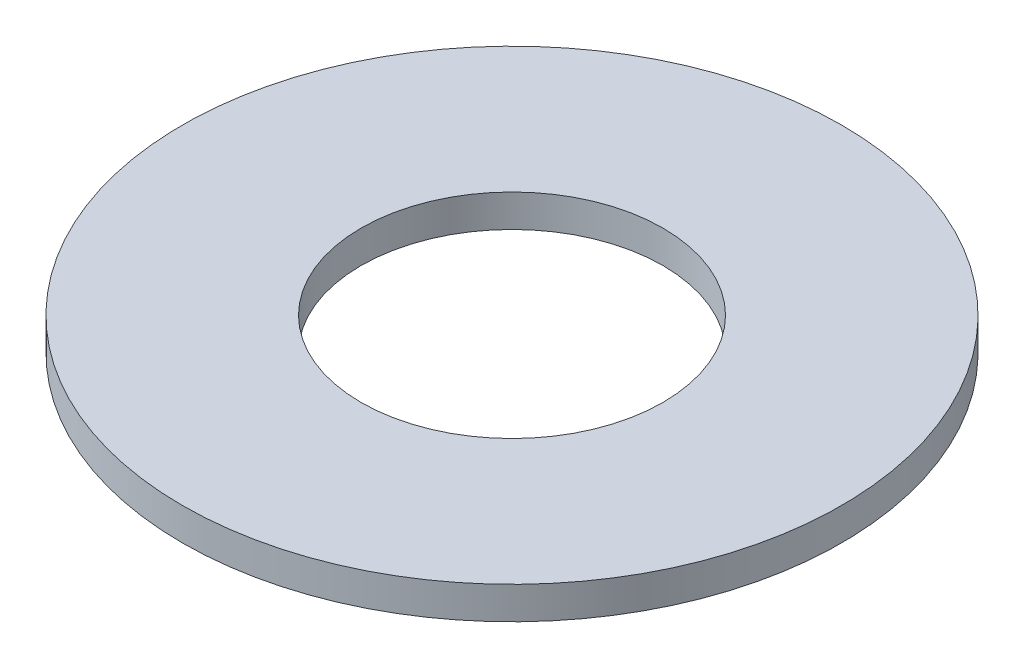
SolidWorks part; units mm, degrees
material "AISI 304"
ref_plane "Front Plane" through (0, 0, 0) normal (0, 0, 1) x (1, 0, 0)
ref_plane "Top Plane" through (0, 0, 0) normal (0, 1, 0) x (1, 0, 0)
ref_plane "Right Plane" through (0, 0, 0) normal (1, 0, 0) x (0, 0, -1)
sketch "Sketch1" plane through (0, 0, 0) normal (0, 1, 0) x (1, 0, 0)
  circle A0 centre (0, 0) radius 1.1811
  circle A1 centre (0, 0) radius 2.5781
  dimension "D1" = 2.3622
  dimension "D2" = 5.1562
extrude "Boss-Extrude1" add sketch "Sketch1" along normal blind 0.254
